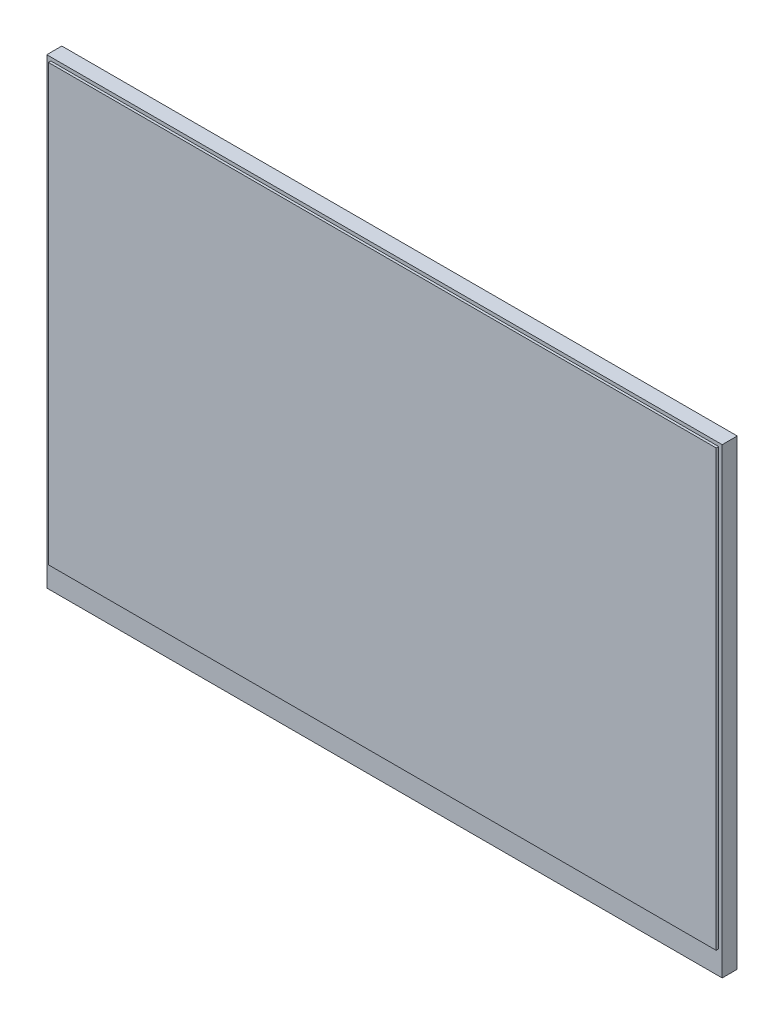
SolidWorks part; units mm, degrees
material "Verre"
ref_plane "Plan de face" through (0, 0, 0) normal (0, 0, 1) x (1, 0, 0)
ref_plane "Plan de dessus" through (0, 0, 0) normal (0, 1, 0) x (1, 0, 0)
ref_plane "Plan de droite" through (0, 0, 0) normal (1, 0, 0) x (0, 0, -1)
sketch "cadremax" plane through (0, 0, 0) normal (0, 0, 1) x (1, 0, 0)
  line L0 (352.4778, 1201.8191) -> (415.2778, 1201.8191) construction
  line L2 (352.4485, 1143.1592) -> (415.2409, 1143.1592)
  line L3 (352.4485, 1143.1592) -> (352.4485, 1186.0993)
  line L4 (352.4485, 1186.0993) -> (415.2409, 1186.0993)
  line L5 (415.2409, 1143.1592) -> (415.2409, 1186.0993)
  dimension "D1" = 62.8
sketch "cadre2" plane through (0, 0, 0) normal (0, 0, 1) x (1, 0, 0)
  line L0 (352.4485, 1143.1592) -> (352.4485, 1186.0993) construction
  line L1 (352.4485, 1144.8202) -> (415.2409, 1144.8202)
  line L2 (352.4485, 1144.8202) -> (352.4485, 1186.0993)
  line L3 (352.4485, 1186.0993) -> (415.2409, 1186.0993)
  line L4 (415.2409, 1144.8202) -> (415.2409, 1186.0993)
sketch "cadreinterne" plane through (0, 0, 0) normal (0, 0, 1) x (1, 0, 0)
  line L1 (352.8348, 1145.3367) -> (414.9082, 1145.3367)
  line L2 (352.8348, 1145.3367) -> (352.8348, 1185.785)
  line L3 (352.8348, 1185.785) -> (414.9082, 1185.785)
  line L4 (414.9082, 1145.3367) -> (414.9082, 1185.785)
extrude "Boss.-Extru.1" add sketch "cadreinterne" along normal blind 0.23
extrude "Boss.-Extru.2" add sketch "cadre2" against normal blind 0.6
extrude "Boss.-Extru.3" add sketch "cadremax" against normal blind 1.4
